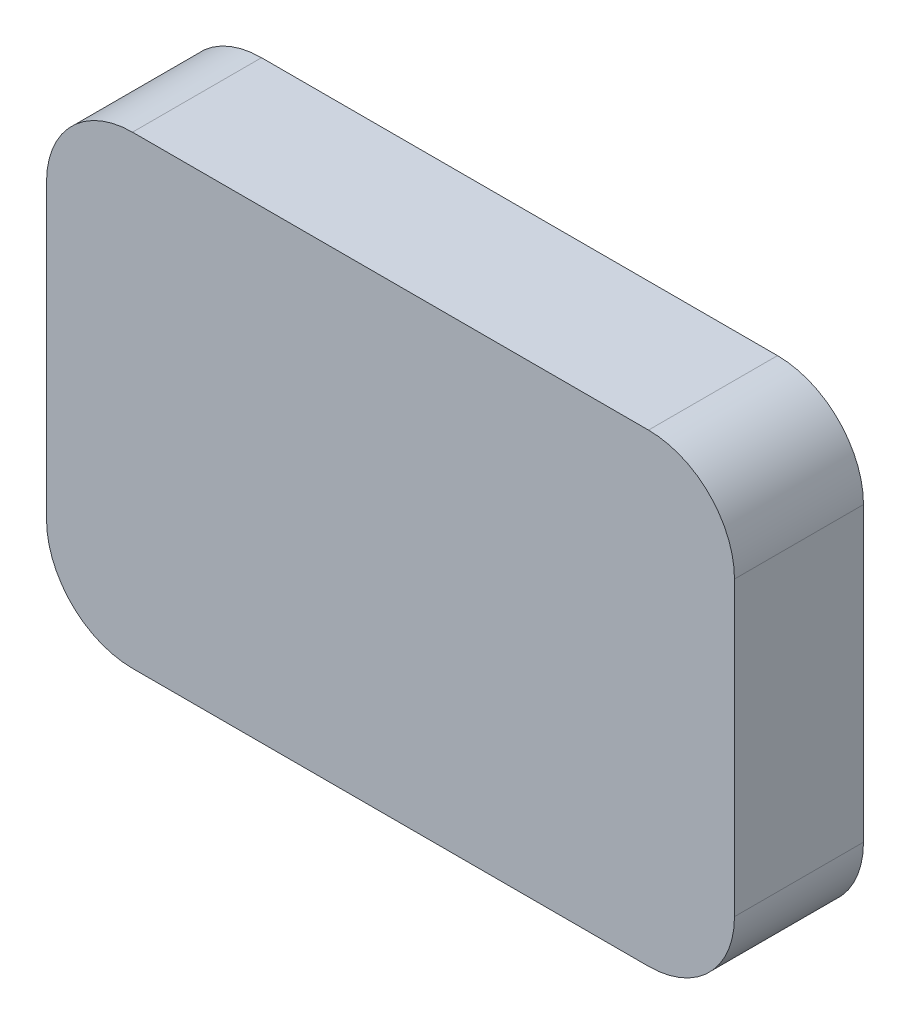
SolidWorks part; units mm, degrees
ref_plane "Front Plane" through (0, 0, 0) normal (0, 0, 1) x (1, 0, 0)
ref_plane "Top Plane" through (0, 0, 0) normal (0, 1, 0) x (1, 0, 0)
ref_plane "Right Plane" through (0, 0, 0) normal (1, 0, 0) x (0, 0, -1)
sketch "Sketch1" plane through (0, 0, 0) normal (0, 0, 1) x (1, 0, 0)
  line L0 (0, 0) -> (80, 0)
  line L1 (80, 0) -> (80, -54)
  line L2 (80, -54) -> (0, -54)
  line L3 (0, -54) -> (0, 0)
  dimension "D1" = 80
  dimension "D2" = 54
extrude "Boss-Extrude1" add sketch "Sketch1" along normal blind 15
fillet "Fillet1" radius 10 4 edges at (80, 0, 7.5) (0, 0, 7.5) (0, -54, 7.5) (80, -54, 7.5)
